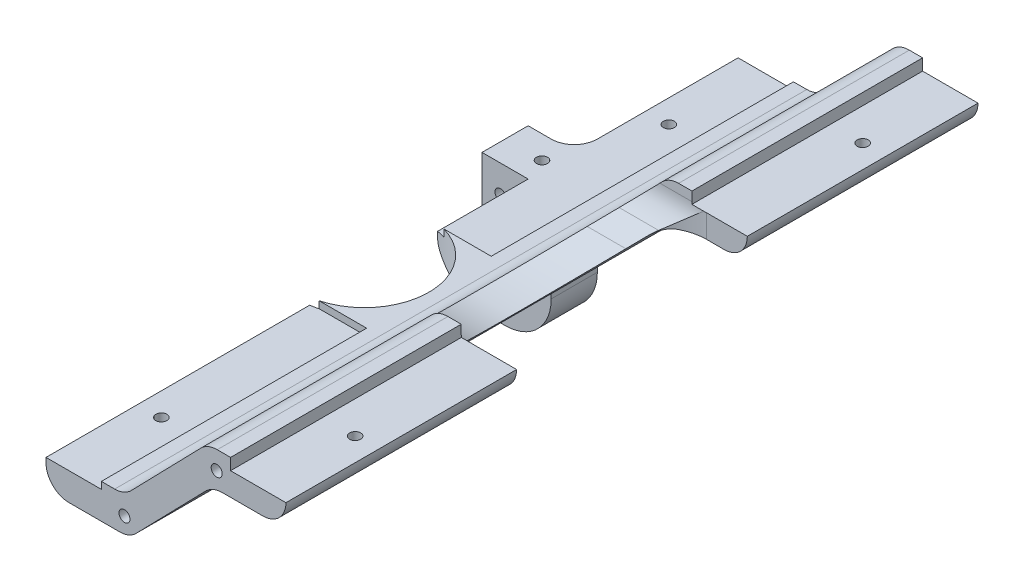
SolidWorks part; units mm, degrees
material "ABS"
ref_plane "Plan de face" through (0, 0, 0) normal (0, 0, 1) x (1, 0, 0)
ref_plane "Plan de dessus" through (0, 0, 0) normal (0, 1, 0) x (1, 0, 0)
ref_plane "Plan de droite" through (0, 0, 0) normal (1, 0, 0) x (0, 0, -1)
sketch "Esquisse1" plane through (0, 0, 0) normal (0, 0, 1) x (1, 0, 0)
  line L0 (-12, 0) -> (0, 0)
  line L1 (0, 0) -> (0, 1.5)
  line L2 (5, 1.5) -> (9.3004, -2.6841) construction
  line L3 (23, 20) -> (28, 20)
  line L4 (28, 18.5) -> (40, 18.5)
  line L5 (40, 18.5) -> (40, 12.5)
  line L6 (40, 12.5) -> (24.0741, 12.5)
  line L7 (24.0741, 12.5) -> (6.0741, -6)
  line L8 (6.0741, -6) -> (-12, -6)
  line L9 (-12, -6) -> (-12, 0)
  line L10 (28, 20) -> (28, 18.5)
  line L11 (0, 1.5) -> (5, 1.5)
  line L12 (5, 1.5) -> (23, 20)
  dimension "D1" = 1.5
  dimension "D2" = 20
  dimension "D3" = 5
  dimension "D4" = 28
  dimension "D5" = 12
  dimension "D6" = 6
extrude "Boss.-Extru.1" add sketch "Esquisse1" along normal mid plane 150
fillet "Congé1" radius 5 6 edges at (40, 12.5, 0) (24.0741, 12.5, 0) (6.0741, -6, 0) (-12, -6, 0) (23, 20, 0) (5, 1.5, 0)
sketch "Esquisse2" plane through (0, 0, 0) normal (0, 1, 0) x (1, 0, 0)
  line L0 (-12, -75) -> (-12, 75) construction
  line L1 (-12, 9.5) -> (0, 9.5)
  line L2 (-12, 9.5) -> (-12, -17.5)
  line L3 (-12, -17.5) -> (0, -17.5)
  line L4 (0, 9.5) -> (0, -17.5)
  line L5 (0, -75) -> (0, 75) construction
  dimension "D1" = 9.5
  dimension "D2" = 17.5
extrude "Boss.-Extru.2" add sketch "Esquisse2" along normal up to surface (1.5 mm away) up to face at (1.4443, 1.5, 0)
sketch "Esquisse3" plane through (0, 1.5, 0) normal (0, 1, 0) x (1, 0, 0)
  line L0 (-12, -17.5) -> (-12, 9.5) construction
  line L1 (0, -75) -> (0, -17.5) construction
  circle A0 centre (-14, -4) radius 14
  point P4 (-12, -4)
  dimension "D1" = 28
extrude "Enlèv. mat.-Extru.1" cut sketch "Esquisse3" against normal through all
sketch "Esquisse4" plane through (40, 0, 0) normal (1, 0, 0) x (0, 0, -1)
  line L0 (-22, 12) -> (-18, 9)
  line L1 (-25, 20) -> (25, 20)
  line L2 (-25, 20) -> (-25, 18)
  line L3 (-75, 20) -> (75, 20) construction
  line L4 (0, 20) -> (0, 3) construction
  line L5 (25, 20) -> (25, 18)
  line L6 (22, 12) -> (18, 9)
  arc A0 (-18, 9) -> (18, 9) centre (0, 33) ccw
  arc A1 (-25, 18) -> (-22, 12) centre (-17.5, 18) ccw
  arc A2 (25, 18) -> (22, 12) centre (17.5, 18) cw
  dimension "D1" = 17
  dimension "D2" = 2
  dimension "D4" = 30
  dimension "D5" = 7.5
  dimension "D3" = 50
extrude "Enlèv. mat.-Extru.2" cut sketch "Esquisse4" against normal through all
sketch "Esquisse5" plane through (0, 20, 0) normal (0, 1, 0) x (1, 0, 0)
  line L0 (21.0541, -25) -> (40, -25) construction
  line L1 (40, 25) -> (31.1631, 25)
  line L2 (40, 25) -> (40, -25)
  line L3 (40, -25) -> (31.1631, -25)
  line L4 (22.6018, 20.649) -> (20.6687, 18) construction
  line L5 (22.6018, 20.649) -> (22.6018, -20.649)
  line L6 (20.6687, -18) -> (22.6018, -20.649) construction
  arc A0 (31.1631, 25) -> (22.6018, 20.649) centre (31.1631, 14.4016) ccw
  arc A1 (22.6018, -20.649) -> (31.1631, -25) centre (31.1631, -14.4016) ccw
extrude "Enlèv. mat.-Extru.3" cut sketch "Esquisse5" against normal through all
sketch "Esquisse6" plane through (0, 0, 75) normal (0, 0, 1) x (1, 0, 0)
  line L0 (21.5277, 18.4868) -> (6.4723, 3.0132) construction
  line L1 (28, 20) -> (25.1113, 20) construction
  line L2 (2.8887, 1.5) -> (0, 1.5) construction
  circle A0 centre (25, 16) radius 1.2
  circle A1 centre (5, -2.5) radius 1.2
  dimension "D1" = 4.2229
  dimension "D2" = 4
  dimension "D3" = 2.4
  dimension "D4" = 4
  dimension "D5" = 2.7894
  dimension "D6" = 5
  dimension "D7" = 25
  dimension "D8" = 18.5
extrude "Enlèv. mat.-Extru.4" cut sketch "Esquisse6" against normal blind 20
sketch "Esquisse7" plane through (0, 18.5, 0) normal (0, 1, 0) x (1, 0, 0)
  line L0 (0, -75) -> (-12, -75) construction
  line L1 (-12, -75) -> (-12, -17.8564) construction
  line L2 (40, -75) -> (40, -25) construction
  line L3 (0, -75) -> (0, -17.5) construction
  line L4 (28, -75) -> (28, -25) construction
  circle A0 centre (35, -55) radius 1.2
  circle A1 centre (-7, -55) radius 1.2
  dimension "D1" = 20
  dimension "D2" = 35
  dimension "D3" = 7
  dimension "D4" = 5
  dimension "D5" = 5
  dimension "D6" = 2.4
  dimension "D7" = 7
  dimension "D8" = 7
extrude "Enlèv. mat.-Extru.5" cut sketch "Esquisse7" against normal through all
mirror "Symétrie1" about plane through (0, 0, 0) normal (0, 0, 1) of "Enlèv. mat.-Extru.5", "Enlèv. mat.-Extru.4"
sketch "Esquisse9" plane through (0, 0, 0) normal (0, 1, 0) x (1, 0, 0)
  line L1 (-7, 29.5) -> (-22, 29.5)
  line L2 (-7, 29.5) -> (-7, 39.5)
  line L3 (-7, 39.5) -> (-22, 39.5)
  line L4 (-22, 29.5) -> (-22, 39.5)
  line L5 (0, 75) -> (-12, 75) construction
  line L6 (-12, 9.8564) -> (-12, 75) construction
  dimension "D1" = 45.5
  dimension "D2" = 10
  dimension "D3" = 10
  dimension "D4" = 15
extrude "Boss.-Extru.3" add sketch "Esquisse9" against normal blind 30
fillet "Congé2" radius 10 2 edges at (-7, -30, -34.5) (-7, -6, -34.5)
fillet "Congé3" radius 5 3 edges at (-12, -0.5, -39.5) (-2, -6, -39.5) (-10.5355, -4.5355, -39.5)
sketch "Esquisse10" plane through (0, 0, -29.5) normal (0, 0, 1) x (1, 0, 0)
  line L0 (-22, -30) -> (-17, -30) construction
  line L1 (-22, -30) -> (-22, 0) construction
  circle A0 centre (-18, -24) radius 1.2
  circle A1 centre (-18, -6) radius 1.2
  dimension "D1" = 18
  dimension "D2" = 6
  dimension "D3" = 4
  dimension "D4" = 2.4
extrude "Enlèv. mat.-Extru.6" cut sketch "Esquisse10" against normal up to surface (10 mm away) up to face at (-13.5544, -13.6727, -39.5)
sketch "Esquisse11" plane through (0, 0, 0) normal (0, 1, 0) x (1, 0, 0)
  line L0 (-22, 34.5) -> (-14, 34.5) construction
  line L1 (-22, 39.5) -> (-22, 29.5) construction
  circle A0 centre (-14, 34.5) radius 1.2
  circle A1 centre (-7, 55) radius 1.2 construction
  dimension "D1" = 8
  dimension "D2" = 7
extrude "Enlèv. mat.-Extru.7" cut sketch "Esquisse11" against normal blind 15
sketch "Esquisse12" plane through (0, 0, 75) normal (0, 0, 1) x (1, 0, 0)
  line L0 (40, 17.5) -> (40, 18.5) construction
  line L1 (28, 20) -> (40, 20)
  line L2 (28, 20) -> (28, 17.5)
  line L3 (28, 17.5) -> (40, 17.5)
  line L4 (40, 20) -> (40, 17.5)
  dimension "D1" = 2.5
extrude "Enlèv. mat.-Extru.8" cut sketch "Esquisse12" against normal through all
